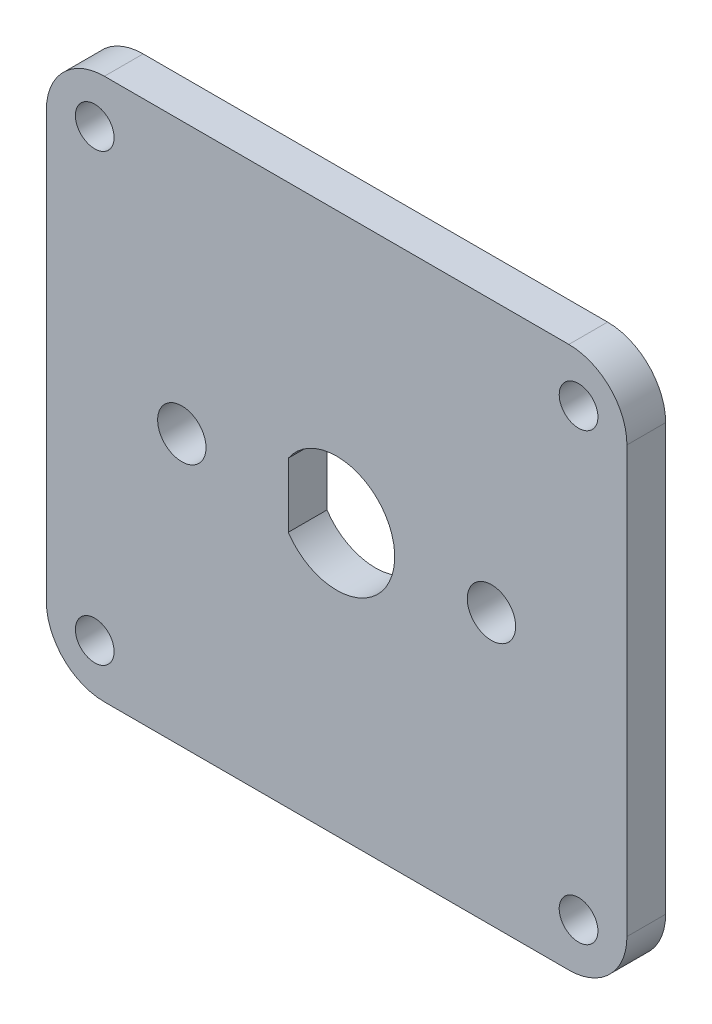
SolidWorks part; units mm, degrees
material "Thornel Mat VMA"
ref_plane "前视基准面" through (0, 0, 0) normal (0, 0, 1) x (1, 0, 0)
ref_plane "上视基准面" through (0, 0, 0) normal (0, 1, 0) x (1, 0, 0)
ref_plane "右视基准面" through (0, 0, 0) normal (1, 0, 0) x (0, 0, -1)
sketch "草图1" plane through (0, 0, 0) normal (0, 0, 1) x (1, 0, 0)
  line L1 (-15, -14) -> (15, -14)
  line L2 (-15, -14) -> (-15, 14)
  line L3 (-15, 14) -> (15, 14)
  line L4 (15, -14) -> (15, 14)
  line L5 (-15, -14) -> (15, 14) construction
  line L6 (-15, 14) -> (15, -14) construction
  point P0 (0, 0)
  dimension "D1" = 28
  dimension "D2" = 30
extrude "凸台-拉伸1" add sketch "草图1" along normal blind 2 contours L2 L3 L4 L1
fillet "圆角1" radius 3 4 edges at (-15, -14, 1) (-15, 14, 1) (15, -14, 1) (15, 14, 1)
sketch "草图2" plane through (0, 0, 2) normal (0, 0, 1) x (1, 0, 0)
  line L0 (0, 17.2036) -> (0, -16.7681) construction
  line L2 (15, -11) -> (15, 11) construction
  line L3 (-12, 14) -> (12, 14) construction
  line L4 (-15, -11) -> (-15, 11) construction
  line L5 (-17.616, 0) -> (20.2601, 0) construction
  circle A4 centre (-12.5, 11.5) radius 1
  circle A5 centre (12.5, 11.5) radius 1
  circle A6 centre (-12.5, -11.5) radius 1
  circle A7 centre (12.5, -11.5) radius 1
  circle A14 centre (8, 0) radius 1.25
  circle A15 centre (-8, 0) radius 1.25
  dimension "D1" = 2
  dimension "D2" = 2.5
  dimension "D5" = 2.5
  dimension "D6" = 2.5
  dimension "D3" = 8
  dimension "D4" = 15
extrude "切除-拉伸1" cut sketch "草图2" against normal blind 10
sketch "草图3" plane through (0, 0, 2) normal (0, 0, 1) x (1, 0, 0)
  line L0 (15, -11) -> (15, 11) construction
  circle A0 centre (0, 0) radius 3
  dimension "D1" = 6
  dimension "D2" = 15
extrude "切除-拉伸2" cut sketch "草图3" against normal blind 10
sketch "草图4" plane through (0, 0, 2) normal (0, 0, 1) x (1, 0, 0)
  line L0 (-2.5, 1.6583) -> (-2.5, -1.6583)
  arc A0 (-2.5, 1.6583) -> (-2.5, -1.6583) centre (0, 0) ccw
  dimension "D2" = 6
  dimension "D1" = 2.5
extrude "凸台-拉伸2" add sketch "草图4" against normal blind 2
